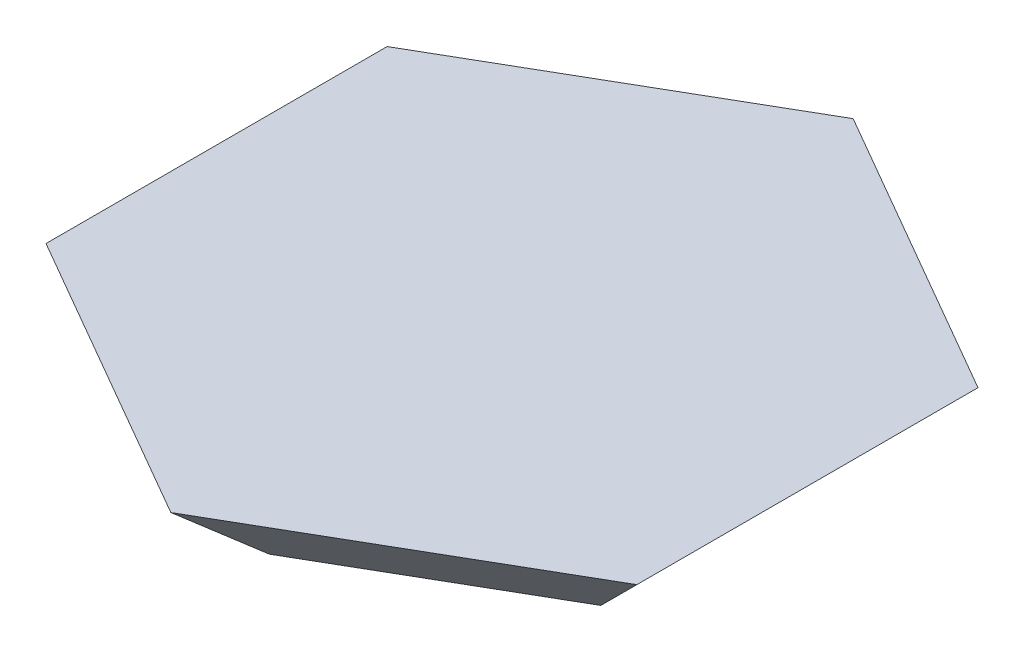
SolidWorks part; units mm, degrees
ref_plane "Plano frontal" through (0, 0, 0) normal (0, 0, 1) x (1, 0, 0)
ref_plane "Plano superior" through (0, 0, 0) normal (0, 1, 0) x (1, 0, 0)
ref_plane "Plano direito" through (0, 0, 0) normal (1, 0, 0) x (0, 0, -1)
sketch "Esboço1" plane through (0, 0, 0) normal (0, 1, 0) x (1, 0, 0)
  line L1 (0, 120) -> (-103.923, 60)
  line L2 (-103.923, 60) -> (-103.923, -60)
  line L3 (-103.923, -60) -> (0, -120)
  line L4 (0, -120) -> (103.923, -60)
  line L5 (103.923, -60) -> (103.923, 60)
  line L6 (103.923, 60) -> (0, 120)
  circle A0 centre (0, 0) radius 103.923 construction
  dimension "D1" = 120
extrude "Ressalto-extrusão1" add sketch "Esboço1" against normal blind 130
chamfer "Chanfro1" distance 30 distance2 30 6 edges at (-103.923, -130, 0) (-51.9615, -130, -90) (51.9615, -130, -90) (103.923, -130, 0) (51.9615, -130, 90) (-51.9615, -130, 90)
sketch "Esboço2" plane through (0, 0, 0) normal (0, 1, 0) x (1, 0, 0)
  line L0 (0, 120) -> (-103.923, 60) construction
  line L1 (0, 108.453) -> (-93.923, 54.2265)
  line L2 (-93.923, 54.2265) -> (-93.923, -54.2265)
  line L3 (-93.923, -54.2265) -> (0, -108.453)
  line L4 (0, -108.453) -> (93.923, -54.2265)
  line L5 (93.923, -54.2265) -> (93.923, 54.2265)
  line L6 (93.923, 54.2265) -> (0, 108.453)
  circle A0 centre (0, 0) radius 93.923 construction
  dimension "D1" = 10
extrude "Corte-extrusão1" cut sketch "Esboço2" against normal blind 50
sketch "Esboço5" plane through (-51.9615, 0, 90) normal (-0.5, 0, 0.866) x (0.866, 0, 0.5)
  line L0 (-60, -100) -> (-60, 0) construction
  line L2 (-60, -100) -> (60, -100) construction
  circle A0 centre (0, -30) radius 15
  dimension "D1" = 30
  dimension "D2" = 60
  dimension "D3" = 70
extrude "Corte-extrusão2" cut sketch "Esboço5" against normal through all
ref_plane "Plano1" through (0, -50, 0) normal (0, 1, 0) x (1, 0, 0)
other "Corte de superfície1"
ref_plane "Plano2" through (0, -100, 0) normal (0, 1, 0) x (1, 0, 0)
other "Corte de superfície2"
shell "Casca1" thickness 10
